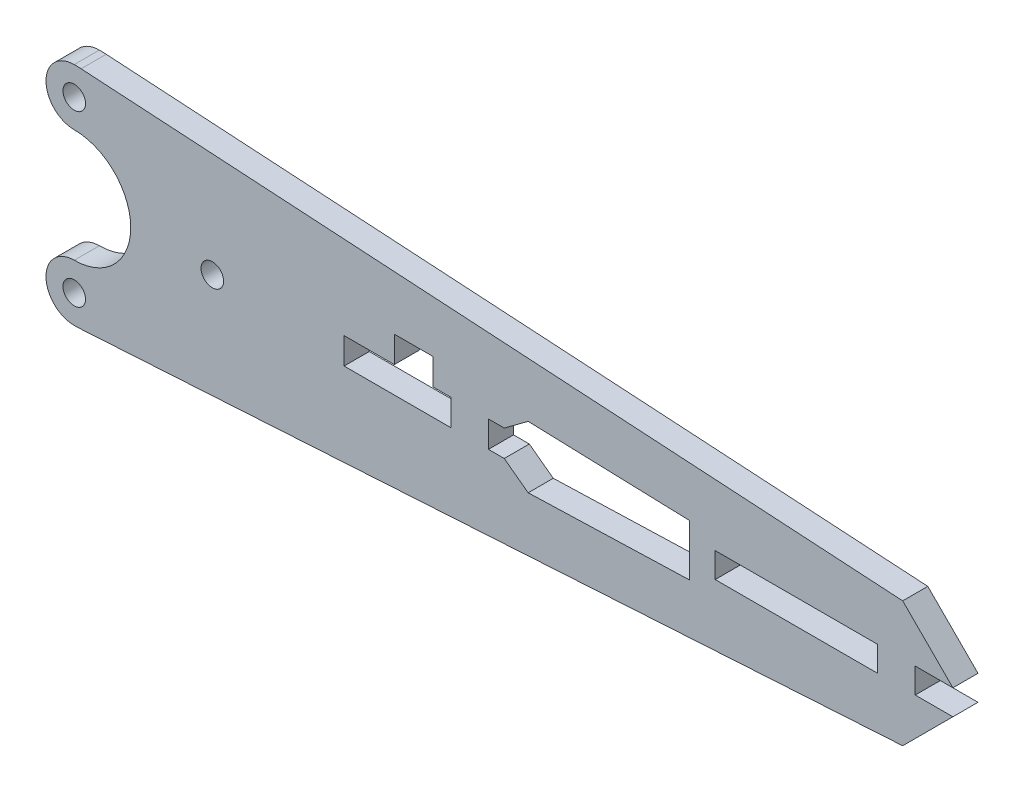
SolidWorks part; units mm, degrees
ref_plane "前视基准面" through (0, 0, 0) normal (0, 0, 1) x (1, 0, 0)
ref_plane "上视基准面" through (0, 0, 0) normal (0, 1, 0) x (1, 0, 0)
ref_plane "右视基准面" through (0, 0, 0) normal (1, 0, 0) x (0, 0, -1)
sketch "草图1" plane through (0, 0, 0) normal (0, 0, 1) x (1, 0, 0)
  line L0 (42, 1) -> (45, 1)
  line L1 (45, 1) -> (41, 5)
  line L2 (41, 5) -> (-24.4533, 8.9834)
  line L3 (5, 1.05) -> (3.6, 1.05)
  line L4 (3.6, 1.05) -> (3.6, 3.15)
  line L5 (0.5, 1.05) -> (-3.5, 1.05)
  line L6 (-3.5, 1.05) -> (-3.5, -1.05)
  line L7 (3.6, 3.15) -> (0.5, 3.15)
  line L8 (0.5, 3.15) -> (0.5, 1.05)
  line L9 (-24.4533, -8.9834) -> (41, -5)
  line L10 (41, -5) -> (45, -1)
  line L11 (45, -1) -> (42, -1)
  line L12 (42, -1) -> (42, 1)
  line L13 (0, 0) -> (36.3378, 0) construction
  line L14 (-3.5, -1.05) -> (5, -1.05)
  line L16 (5, 1.05) -> (5, -1.05)
  line L20 (39, 1) -> (39, -1)
  line L22 (39, -1) -> (26.0619, -1)
  line L23 (26.0619, 1) -> (39, 1)
  line L24 (26.0619, -1) -> (26.0619, 1)
  line L25 (24.0309, -2.05) -> (11.1621, -2.4631)
  line L26 (24.0309, 2.05) -> (24.0309, -2.05)
  line L27 (9.2566, -1.05) -> (7.9988, -1.05)
  line L28 (9.2566, -1.05) -> (11.1621, -2.4631)
  line L29 (11.1621, 2.4631) -> (9.2566, 1.05)
  line L30 (11.1621, 2.4631) -> (24.0309, 2.05)
  line L31 (7.9988, 1.05) -> (9.2566, 1.05)
  line L32 (7.9988, 1.05) -> (7.9988, -1.05)
  circle A0 centre (-25, 6.75) radius 0.9
  arc A1 (-25, 9) -> (-25, 4.5) centre (-25, 6.75) ccw
  circle A2 centre (-25, -6.75) radius 0.9
  arc A3 (-25, -9) -> (-25, -4.5) centre (-25, -6.75) cw
  circle A4 centre (-14, 0) radius 0.9
  arc A11 (-25, -4.5) -> (-25, 4.5) centre (-25, 0) ccw
  arc A12 (-24.4533, 8.9834) -> (-25, 9) centre (-25, 0) ccw
  arc A13 (-25, -9) -> (-24.4533, -8.9834) centre (-25, 0) ccw
  dimension "D2" = 3.1
  dimension "D5" = 8.5
  dimension "D6" = 2.9988
  dimension "D13" = 18
  dimension "D9" = 13.5
  dimension "D16" = 1.8
  dimension "D15" = 4.5
  dimension "D17" = 39
  dimension "D19" = 11
  dimension "D20" = 1.8
  dimension "D3" = 2.1
  dimension "D4" = 2
  dimension "D7" = 2.1
  dimension "D8" = 3
  dimension "D10" = 25
  dimension "D11" = 30
  dimension "D12" = 70
  dimension "D14" = 10
  dimension "D18" = 4
extrude "凸台-拉伸1" add sketch "草图1" along normal blind 2
